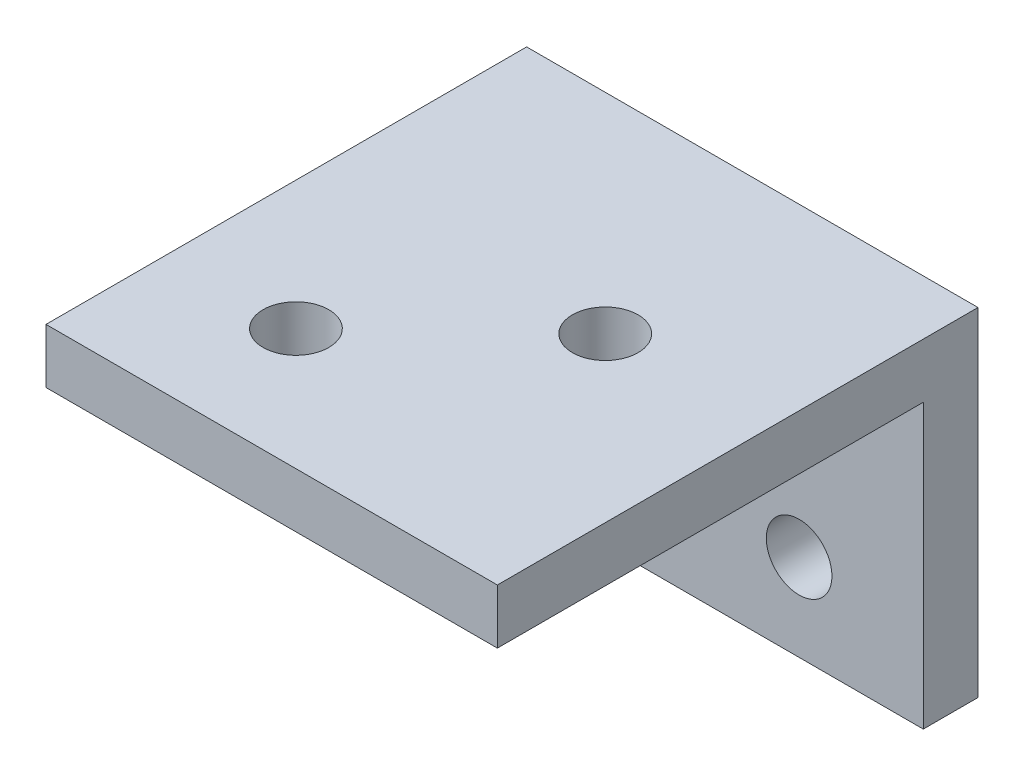
SolidWorks part; units mm, degrees
ref_plane "Front Plane" through (0, 0, 0) normal (0, 0, 1) x (1, 0, 0)
ref_plane "Top Plane" through (0, 0, 0) normal (0, 1, 0) x (1, 0, 0)
ref_plane "Right Plane" through (0, 0, 0) normal (1, 0, 0) x (0, 0, -1)
sketch "Sketch1" plane through (0, 0, 0) normal (0, 0, 1) x (1, 0, 0)
  line L2 (75.811, -27.5265) -> (94.3666, -27.5265) construction
  line L4 (64.4604, -35.464) -> (105.7172, -35.464)
  line L5 (64.4604, -35.464) -> (64.4604, -19.5889)
  line L6 (64.4604, -19.5889) -> (105.7172, -19.5889)
  line L7 (105.7172, -35.464) -> (105.7172, -19.5889)
  line L8 (64.4604, -35.464) -> (105.7172, -19.5889) construction
  line L9 (64.4604, -19.5889) -> (105.7172, -35.464) construction
  circle A0 centre (94.3666, -27.5265) radius 3
  circle A1 centre (75.811, -27.5265) radius 3
  circle A2 centre (75.811, -27.5265) radius 1.54 construction
  circle A3 centre (94.3666, -27.5265) radius 1.54 construction
  point P5 (85.0888, -27.5265)
  dimension "D1" = 6
  dimension "D2" = 6
  dimension "D3" = 18.5556
extrude "Boss-Extrude1" add sketch "Sketch1" along normal blind 5
sketch "Sketch2" plane through (0, 0, 5) normal (0, 0, 1) x (1, 0, 0)
  line L0 (64.4604, -35.464) -> (105.7172, -35.464) construction
  line L1 (64.4604, -35.464) -> (105.7172, -35.464)
  line L2 (64.4604, -35.464) -> (64.4604, -50.464)
  line L3 (64.4604, -50.464) -> (105.7172, -50.464)
  line L4 (105.7172, -35.464) -> (105.7172, -50.464)
  line L5 (105.7172, -35.464) -> (105.7172, -19.5889) construction
  line L6 (64.4604, -19.5889) -> (64.4604, -35.464) construction
  dimension "D1" = 15
extrude "Boss-Extrude3" add sketch "Sketch2" against normal up to vertex (5 mm away) up to point (64.4604, -35.464, 0)
sketch "Sketch3" plane through (0, -50.464, 0) normal (0, -1, 0) x (1, 0, 0)
  line L0 (105.7172, 5) -> (64.4604, 5) construction
  line L1 (64.4604, 5) -> (64.4604, 0) construction
  line L2 (84.796, 27.3644) -> (54.9427, 27.3644) construction
  line L3 (105.7172, 5) -> (64.4604, 5)
  line L5 (105.7172, 5) -> (64.4604, 5)
  line L6 (105.7172, 5) -> (105.7172, 43.9312)
  line L7 (105.7172, 43.9312) -> (64.4604, 43.9312)
  line L8 (64.4604, 5) -> (64.4604, 43.9312)
  line L9 (64.4604, 43.9312) -> (105.7172, 5) construction
  line L10 (84.796, 27.3644) -> (77.5055, 19.6385) construction
  circle A4 centre (76.2138, 32.8403) radius 3
  circle A5 centre (90.76, 19.1141) radius 3
  dimension "D1" = 6
  dimension "D2" = 20
extrude "Boss-Extrude5" add sketch "Sketch3" against normal blind 5
mirror "Mirror1" about plane through (64.4604, -19.5889, 5) normal (0, -1, 0) of bodies 104
delete or keep bodies "Body-Delete/Keep 1" type delete bodies bodies 104
